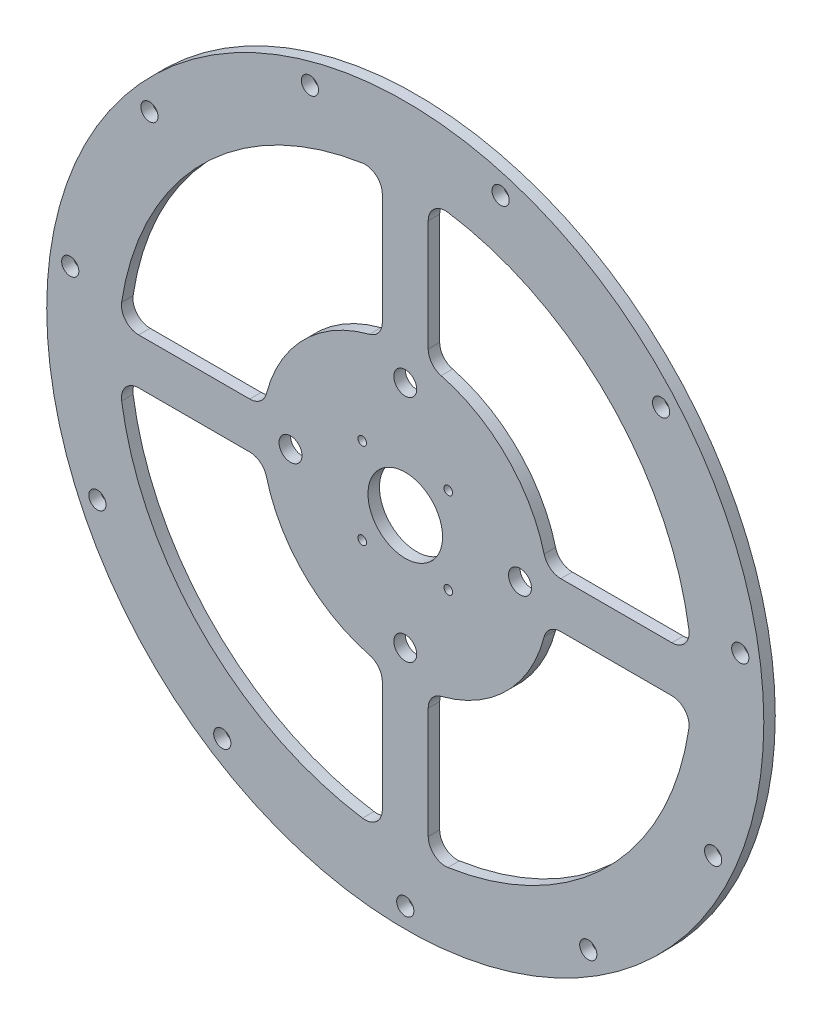
SolidWorks part; units mm, degrees
ref_plane "前视基准面" through (0, 0, 0) normal (0, 0, 1) x (1, 0, 0)
ref_plane "上视基准面" through (0, 0, 0) normal (0, 1, 0) x (1, 0, 0)
ref_plane "右视基准面" through (0, 0, 0) normal (1, 0, 0) x (0, 0, -1)
sketch "草图1" plane through (0, 0, 0) normal (0, 0, 1) x (1, 0, 0)
  line L0 (0, 0) -> (-27.6423, -27.6423) construction
  line L1 (0, 0) -> (0, -5.1352) construction
  line L2 (0, 0) -> (-102.4397, 0) construction
  line L3 (0, 1.2542) -> (0, 77.8801) construction
  line L4 (0, 0) -> (118.6635, 0) construction
  line L5 (0, 0) -> (0, -124.4057) construction
  line L6 (-46.4758, 4) -> (-27.1109, 4)
  line L7 (4, 46.4758) -> (4, 27.1109)
  line L8 (-27.1109, -4) -> (-46.4758, -4)
  line L9 (-4, 27.1109) -> (-4, 46.4758)
  line L10 (46.4758, -4) -> (27.1109, -4)
  line L11 (27.1109, 4) -> (46.4758, 4)
  line L12 (-4, -46.4758) -> (-4, -27.1109)
  line L13 (4, -27.1109) -> (4, -46.4758)
  circle A0 centre (0, 0) radius 59 construction
  circle A1 centre (0, 0) radius 20 construction
  circle A2 centre (0, 0) radius 62.5
  circle A3 centre (0, -20) radius 2
  circle A4 centre (0, -59) radius 1.5
  circle A5 centre (-20, 0) radius 2
  circle A6 centre (0, 20) radius 2
  circle A7 centre (20, 0) radius 2
  circle A8 centre (-31.8978, -49.634) radius 1.5
  circle A9 centre (-53.6683, -24.5095) radius 1.5
  circle A10 centre (-58.3995, 8.3966) radius 1.5
  circle A11 centre (-44.5892, 38.6368) radius 1.5
  circle A12 centre (-16.6222, 56.6101) radius 1.5
  circle A13 centre (16.6222, 56.6101) radius 1.5
  circle A14 centre (44.5892, 38.6368) radius 1.5
  circle A15 centre (58.3995, 8.3966) radius 1.5
  circle A16 centre (53.6683, -24.5095) radius 1.5
  circle A17 centre (31.8978, -49.634) radius 1.5
  circle A18 centre (0, 0) radius 6.5
  circle A19 centre (0, 0) radius 10.6045 construction
  circle A21 centre (-7.4985, -7.4985) radius 0.75
  circle A22 centre (-7.4985, 7.4985) radius 0.75
  circle A23 centre (7.4985, 7.4985) radius 0.75
  circle A24 centre (7.4985, -7.4985) radius 0.75
  circle A25 centre (0, 0) radius 50 construction
  circle A26 centre (0, 0) radius 25 construction
  arc A27 (-49.4423, 7.4468) -> (-7.4468, 49.4423) centre (0, 0) cw
  arc A28 (-24.2061, 6.25) -> (-6.25, 24.2061) centre (0, 0) cw
  arc A29 (6.25, 24.2061) -> (24.2061, 6.25) centre (0, 0) cw
  arc A30 (7.4468, 49.4423) -> (49.4423, 7.4468) centre (0, 0) cw
  arc A31 (24.2061, -6.25) -> (6.25, -24.2061) centre (0, 0) cw
  arc A32 (49.4423, -7.4468) -> (7.4468, -49.4423) centre (0, 0) cw
  arc A33 (-6.25, -24.2061) -> (-24.2061, -6.25) centre (0, 0) cw
  arc A34 (-7.4468, -49.4423) -> (-49.4423, -7.4468) centre (0, 0) cw
  arc A35 (7.4468, 49.4423) -> (4, 46.4758) centre (7, 46.4758) ccw
  arc A36 (6.25, 24.2061) -> (4, 27.1109) centre (7, 27.1109) cw
  arc A37 (49.4423, 7.4468) -> (46.4758, 4) centre (46.4758, 7) cw
  arc A38 (27.1109, 4) -> (24.2061, 6.25) centre (27.1109, 7) cw
  arc A39 (49.4423, -7.4468) -> (46.4758, -4) centre (46.4758, -7) ccw
  arc A40 (24.2061, -6.25) -> (27.1109, -4) centre (27.1109, -7) cw
  arc A41 (6.25, -24.2061) -> (4, -27.1109) centre (7, -27.1109) ccw
  arc A42 (7.4468, -49.4423) -> (4, -46.4758) centre (7, -46.4758) cw
  arc A43 (-6.25, -24.2061) -> (-4, -27.1109) centre (-7, -27.1109) cw
  arc A44 (-7.4468, -49.4423) -> (-4, -46.4758) centre (-7, -46.4758) ccw
  arc A45 (-24.2061, -6.25) -> (-27.1109, -4) centre (-27.1109, -7) ccw
  arc A46 (-49.4423, -7.4468) -> (-46.4758, -4) centre (-46.4758, -7) cw
  arc A47 (-27.1109, 4) -> (-24.2061, 6.25) centre (-27.1109, 7) ccw
  arc A48 (-6.25, 24.2061) -> (-4, 27.1109) centre (-7, 27.1109) ccw
  arc A49 (-4, 46.4758) -> (-7.4468, 49.4423) centre (-7, 46.4758) ccw
  arc A50 (-49.4423, 7.4468) -> (-46.4758, 4) centre (-46.4758, 7) ccw
  point P94 (-24.6779, -4)
  point P97 (-49.8397, -4)
  point P100 (-24.6779, 4)
  point P107 (-49.8397, 4)
  dimension "D1" = 125
  dimension "D2" = 118
  dimension "D3" = 40
  dimension "D4" = 4
  dimension "D5" = 3
  dimension "D8" = 13
  dimension "D9" = 21.209
  dimension "D10" = 1.5
  dimension "D12" = 4
  dimension "D14" = 50
  dimension "D15" = 100
  dimension "D17" = 4
  dimension "D18" = 3
  dimension "D11" = 4
  dimension "D13" = 4
  dimension "D6" = 4
  dimension "D7" = 11
  dimension "D16" = 4
extrude "凸台-拉伸1" add sketch "草图1" along normal blind 2 contours A2
